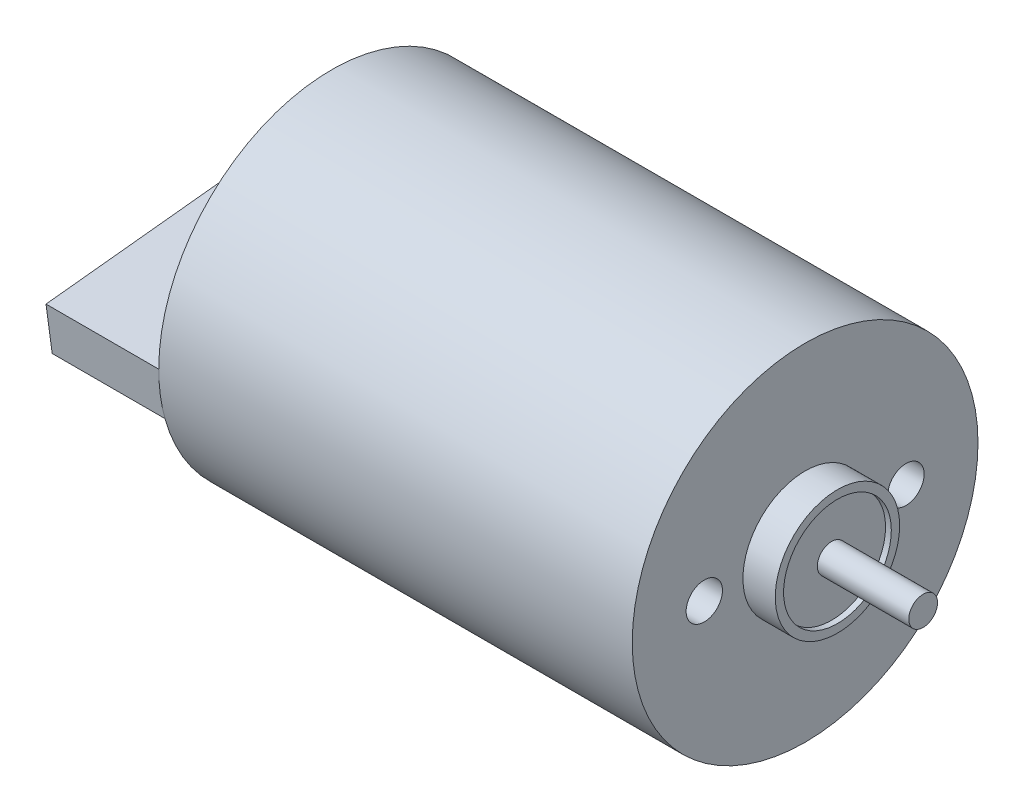
SolidWorks part; units mm, degrees
ref_plane "Front Plane" through (0, 0, 0) normal (0, 0, 1) x (1, 0, 0)
ref_plane "Top Plane" through (0, 0, 0) normal (0, 1, 0) x (1, 0, 0)
ref_plane "Right Plane" through (0, 0, 0) normal (1, 0, 0) x (0, 0, -1)
sketch "Sketch1" plane through (0, 0, 0) normal (1, 0, 0) x (0, 0, -1)
  circle A0 centre (0, 0) radius 13.8
  dimension "D1" = 27.6
extrude "Boss-Extrude1" add sketch "Sketch1" along normal blind 37.8
sketch "Sketch2" plane through (37.8, 0, 0) normal (1, 0, 0) x (0, 0, -1)
  circle A0 centre (0, 0) radius 4.965
  dimension "D1" = 9.93
extrude "Boss-Extrude2" add sketch "Sketch2" along normal blind 2.58
sketch "Sketch3" plane through (40.38, 0, 0) normal (1, 0, 0) x (0, 0, -1)
  circle A0 centre (0, 0) radius 4.3
  dimension "D1" = 8.6
extrude "Cut-Extrude1" cut sketch "Sketch3" against normal blind 0.46
sketch "Sketch4" plane through (39.92, 0, 0) normal (1, 0, 0) x (0, 0, -1)
  circle A0 centre (0, 0) radius 1.15
  dimension "D1" = 2.3
extrude "Boss-Extrude3" add sketch "Sketch4" along normal blind 7.3
hole_wizard "M2.5 Clearance Hole1" positions "Sketch5" profile "Sketch6" hole size "M2.5" standard "ANSI Metric"
sketch "Sketch5" plane through (37.8, 0, 0) normal (1, 0, 0) x (0, 0, -1)
  line L0 (-8.05, 0) -> (8.05, 0) construction
  point P1 (-8.05, 0)
  point P2 (8.05, 0)
  dimension "D1" = 16.1
  dimension "D2" = 8.05
sketch "Sketch6" plane through (37.8, 0, 8.05) normal (0, 1, 0) x (0, 0, -1)
  line L0 (0, 0) -> (0, 10.8712)
  line L1 (0, 10.8712) -> (1.45, 10)
  line L2 (1.45, 10) -> (1.45, 0)
  line L5 (1.45, 0) -> (0, 0)
  line L10 (0, 10.8712) -> (-1.45, 10) construction
  line L11 (0, -6.35) -> (0, 107.95) construction
  dimension "Hole Dia." = 2.9
  dimension "Hole Depth" = 10
  dimension "Drill Angle" = 118
sketch "Sketch7" plane through (0, 0, 0) normal (-1, 0, 0) x (0, 0, 1)
  line L0 (-13.4871, 2.9221) -> (13.8, 0)
  line L1 (13.8, 0) -> (13.3039, -3.6669)
  line L2 (13.3039, -3.6669) -> (-12.668, -5.4736)
  line L3 (-12.668, -5.4736) -> (-13.4871, 2.9221)
  circle A0 centre (0, 0) radius 13.8 construction
extrude "Boss-Extrude4" add sketch "Sketch7" along normal blind 9
equation "\"D2@Sketch5\"=\"D1@Sketch5\"/2"
